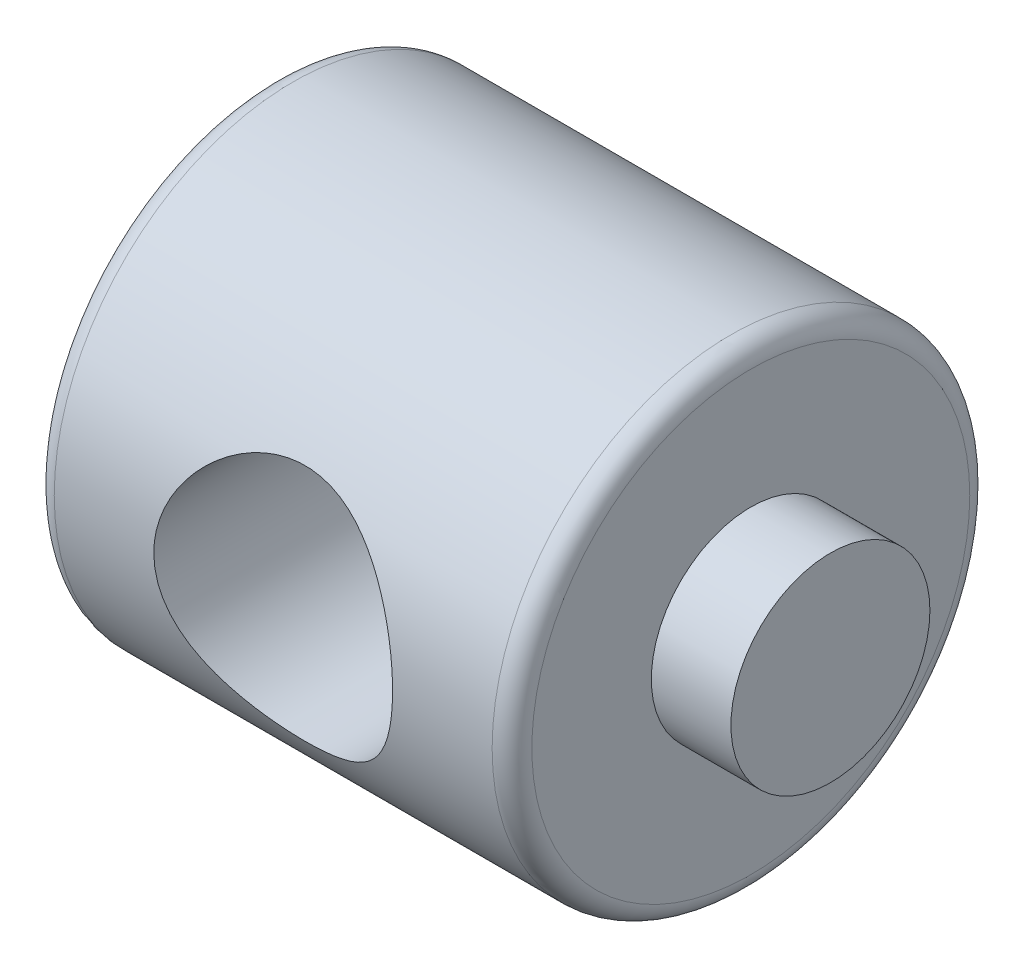
SolidWorks part; units mm, degrees
ref_plane "Front Plane" through (0, 0, 0) normal (0, 0, 1) x (1, 0, 0)
ref_plane "Top Plane" through (0, 0, 0) normal (0, 1, 0) x (1, 0, 0)
ref_plane "Right Plane" through (0, 0, 0) normal (1, 0, 0) x (0, 0, -1)
sketch "Sketch1" plane through (0, 0, 0) normal (1, 0, 0) x (0, 0, -1)
  circle A0 centre (0, 0) radius 9.525
  dimension "D1" = 19.05
extrude "Boss-Extrude1" add sketch "Sketch1" along normal mid plane 19.05
sketch "Sketch2" plane through (9.525, 0, 0) normal (1, 0, 0) x (0, 0, -1)
  circle A0 centre (0, 0) radius 3.9688
  dimension "D1" = 7.9375
extrude "Boss-Extrude2" add sketch "Sketch2" along normal blind 3.175
sketch "Sketch3" plane through (-9.525, 0, 0) normal (-1, 0, 0) x (0, 0, 1)
  circle A0 centre (0, 0) radius 3.9688
  dimension "D1" = 7.9375
fillet "Fillet1" radius 0.7925 2 edges at (-9.525, 0, -9.525) (9.525, 0, -9.525)
ref_plane "Plane3" through (0, 0, 9.525) normal (0, 0, 1) x (1, 0, 0)
extrude "Boss-Extrude3" add sketch "Sketch3" along normal blind 3.175
sketch "Sketch13" plane through (0, 0, 0) normal (0, 0, 1) x (1, 0, 0)
  circle A0 centre (0, 0) radius 4.7625
  dimension "D1" = 9.525
extrude "Cut-Extrude1" cut sketch "Sketch13" along normal through all both and the other way through all contours A0
